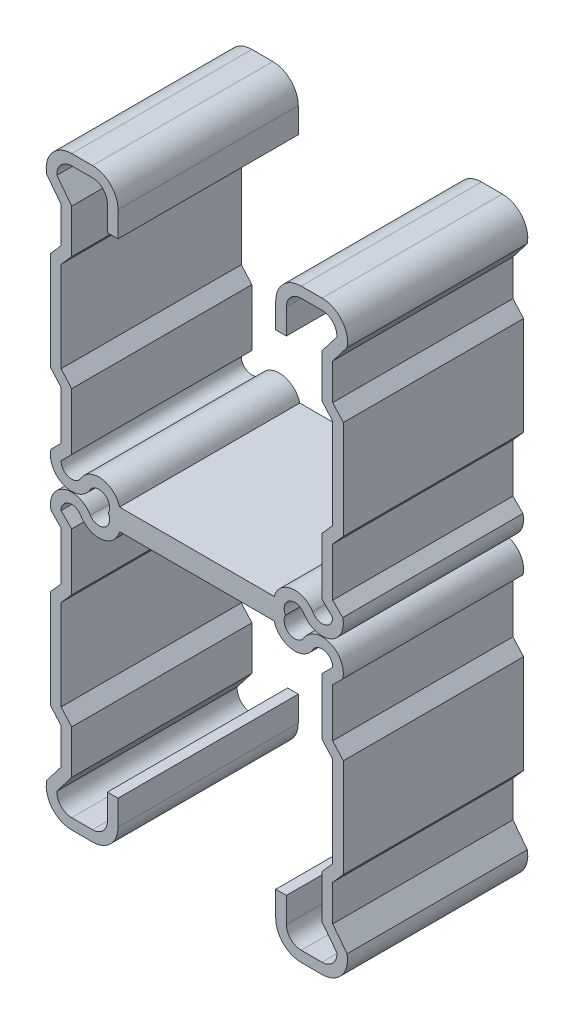
SolidWorks part; units mm, degrees
ref_plane "Plane1" through (0, 0, 0) normal (0, 0, 1) x (1, 0, 0)
ref_plane "Plane2" through (0, 0, 0) normal (0, 1, 0) x (1, 0, 0)
ref_plane "Plane3" through (0, 0, 0) normal (1, 0, 0) x (0, 0, -1)
sketch "Sketch1" plane through (0, 0, 0) normal (0, 0, 1) x (1, 0, 0)
  line L0 (17.6403, 16.3393) -> (19.7299, 19.0635)
  line L1 (17.6403, -13.9795) -> (19.1389, -15.4781)
  line L2 (-17.6403, -13.9795) -> (-19.1389, -15.4781)
  line L4 (-17.6403, -13.9795) -> (-17.6403, -5.9368)
  line L5 (17.6403, 21.2598) -> (14.7033, 21.2598)
  line L6 (12.6111, 19.1676) -> (12.6111, 15.6147)
  line L7 (-17.6403, -5.9368) -> (-19.1389, -4.2539)
  line L8 (-12.6111, 19.1676) -> (-12.6111, 15.6147)
  line L9 (0, 10.16) -> (0, -7.62) construction
  line L10 (-19.1389, -4.2539) -> (-19.1389, 8.4957)
  line L11 (-17.6403, 10.1786) -> (-19.1389, 8.4957)
  line L12 (-17.6403, 10.1786) -> (-17.6403, 16.3393)
  line L13 (-17.6403, 16.3393) -> (-19.7299, 19.0635)
  line L14 (-17.6403, 21.2598) -> (-14.7033, 21.2598)
  line L16 (17.6403, -13.9795) -> (17.6403, -5.9368)
  line L17 (17.6403, 10.1786) -> (17.6403, 16.3393)
  line L18 (-11.1125, 19.1676) -> (-11.1125, 15.6147)
  line L19 (-17.6403, 22.7584) -> (-14.7033, 22.7584)
  line L20 (-19.1389, 15.8307) -> (-21.1624, 18.4689)
  line L21 (-19.1389, 10.7491) -> (-19.1389, 15.8307)
  line L22 (-19.1389, 10.7491) -> (-20.6375, 9.0662)
  line L23 (-20.6375, -4.8244) -> (-20.6375, 9.0662)
  line L24 (-19.1389, -6.5073) -> (-20.6375, -4.8244)
  line L25 (19.1389, -4.2539) -> (19.1389, 8.4957)
  line L26 (-19.1389, -13.3588) -> (-19.1389, -6.5073)
  line L27 (-19.1389, -13.3588) -> (-20.5535, -14.7733)
  line L28 (11.1125, 19.1676) -> (11.1125, 15.6147)
  line L29 (17.6403, 22.7584) -> (14.7033, 22.7584)
  line L30 (19.1389, 15.8307) -> (21.1624, 18.4689)
  line L31 (19.1389, 10.7491) -> (19.1389, 15.8307)
  line L32 (19.1389, 10.7491) -> (20.6375, 9.0662)
  line L33 (20.6375, -4.8244) -> (20.6375, 9.0662)
  line L34 (19.1389, -6.5073) -> (20.6375, -4.8244)
  line L35 (19.1389, -13.3588) -> (19.1389, -6.5073)
  line L36 (19.1389, -13.3588) -> (20.5535, -14.7733)
  line L37 (17.6403, -5.9368) -> (19.1389, -4.2539)
  line L38 (-12.4806, -18.5166) -> (12.4806, -18.5166)
  line L39 (17.6403, 10.1786) -> (19.1389, 8.4957)
  line L41 (-10.899, -17.018) -> (10.899, -17.018)
  line L42 (-12.6111, 15.6147) -> (-11.1125, 15.6147)
  line L43 (11.1125, 15.6147) -> (12.6111, 15.6147)
  arc A0 (19.1389, -15.4781) -> (16.3052, -16.1588) centre (17.6403, -15.4781) cw
  arc A1 (16.3052, -16.1588) -> (10.899, -17.018) centre (13.7938, -17.7947) ccw
  arc A2 (-16.4143, -16.3399) -> (-10.899, -17.018) centre (-13.7938, -17.7947) cw
  arc A3 (-19.1389, -15.4781) -> (-16.4143, -16.3399) centre (-17.6403, -15.4781) ccw
  arc A4 (-17.6403, 21.2598) -> (-19.7299, 19.0635) centre (-17.6403, 19.1676) ccw
  arc A5 (-12.6111, 19.1676) -> (-14.7033, 21.2598) centre (-14.7033, 19.1676) ccw
  arc A6 (17.6403, 21.2598) -> (19.7299, 19.0635) centre (17.6403, 19.1676) cw
  arc A7 (12.6111, 19.1676) -> (14.7033, 21.2598) centre (14.7033, 19.1676) cw
  arc A8 (-11.1125, 19.1676) -> (-14.7033, 22.7584) centre (-14.7033, 19.1676) ccw
  arc A9 (-17.6403, 22.7584) -> (-21.1624, 18.4689) centre (-17.6403, 19.1676) ccw
  arc A10 (-20.5535, -14.7733) -> (-15.0198, -16.9329) centre (-17.6403, -15.4781) ccw
  arc A11 (11.1125, 19.1676) -> (14.7033, 22.7584) centre (14.7033, 19.1676) cw
  arc A12 (17.6403, 22.7584) -> (21.1624, 18.4689) centre (17.6403, 19.1676) cw
  arc A13 (20.5535, -14.7733) -> (15.0198, -16.9329) centre (17.6403, -15.4781) cw
  arc A14 (15.0198, -16.9329) -> (12.4806, -18.5166) centre (13.7938, -17.7947) ccw
  arc A15 (-15.0198, -16.9329) -> (-12.4806, -18.5166) centre (-13.7938, -17.7947) cw
  dimension "D9" = 7.1437
  dimension "base" = 18.5166
  dimension "D5" = 9.525
  dimension "ToeHt" = 22.7584
  dimension "D6" = 22.225
  dimension "D8" = 15.4781
  dimension "D12" = 41.275
  dimension "D14" = 13.6922
  dimension "D15" = 13.8906
extrude "Base-Extrude" add sketch "Sketch1" along normal mid plane 25.4
ref_plane "Plane4" through (0, -18.5166, 0) normal (0, -1, 0) x (1, 0, 0)
mirror "Mirror1" about plane through (0, -18.5166, 0) normal (0, -1, 0) of "Base-Extrude"
